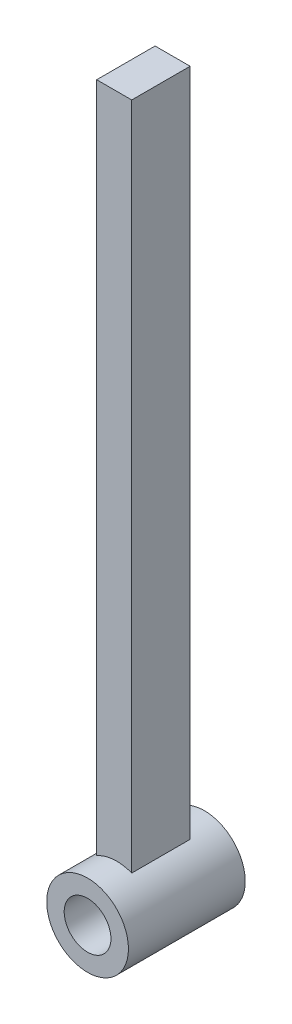
SolidWorks part; units mm, degrees
ref_plane "Plan de face" through (0, 0, 0) normal (0, 0, 1) x (1, 0, 0)
ref_plane "Plan de dessus" through (0, 0, 0) normal (0, 1, 0) x (1, 0, 0)
ref_plane "Plan de droite" through (0, 0, 0) normal (1, 0, 0) x (0, 0, -1)
sketch "Esquisse1" plane through (0, 0, 0) normal (0, 0, 1) x (1, 0, 0)
  line L0 (0, 0) -> (0, 55)
  line L1 (0, 55) -> (3, 55)
  line L2 (3, 55) -> (3, 0)
  line L3 (3, 0) -> (0, 0)
  dimension "D1" = 55
  dimension "D2" = 3
extrude "Boss.-Extru.1" add sketch "Esquisse1" along normal mid plane 5
sketch "Esquisse2" plane through (0, 0, 0) normal (0, 0, 1) x (1, 0, 0)
  circle A0 centre (1.7187, -5.5822) radius 3.5
  circle A1 centre (1.7187, -5.5822) radius 2
  dimension "D1" = 4
  dimension "D2" = 7
extrude "Boss.-Extru.2" add sketch "Esquisse2" along normal mid plane 10 separate body
sketch "Esquisse3" plane through (0, 0, 0) normal (0, -1, 0) x (1, 0, 0)
  line L4 (0, -2.5) -> (3, -2.5)
  line L5 (3, -2.5) -> (3, 2.5)
  line L6 (3, 2.5) -> (0, 2.5)
  line L7 (0, 2.5) -> (0, -2.5)
  line L8 (0, -2.5) -> (3, -2.5)
  line L9 (3, -2.5) -> (3, 2.5)
  line L10 (3, 2.5) -> (0, 2.5)
  line L11 (0, 2.5) -> (0, -2.5)
  dimension "D1" = 0
extrude "Boss.-Extru.3" add sketch "Esquisse3" along normal up to next
